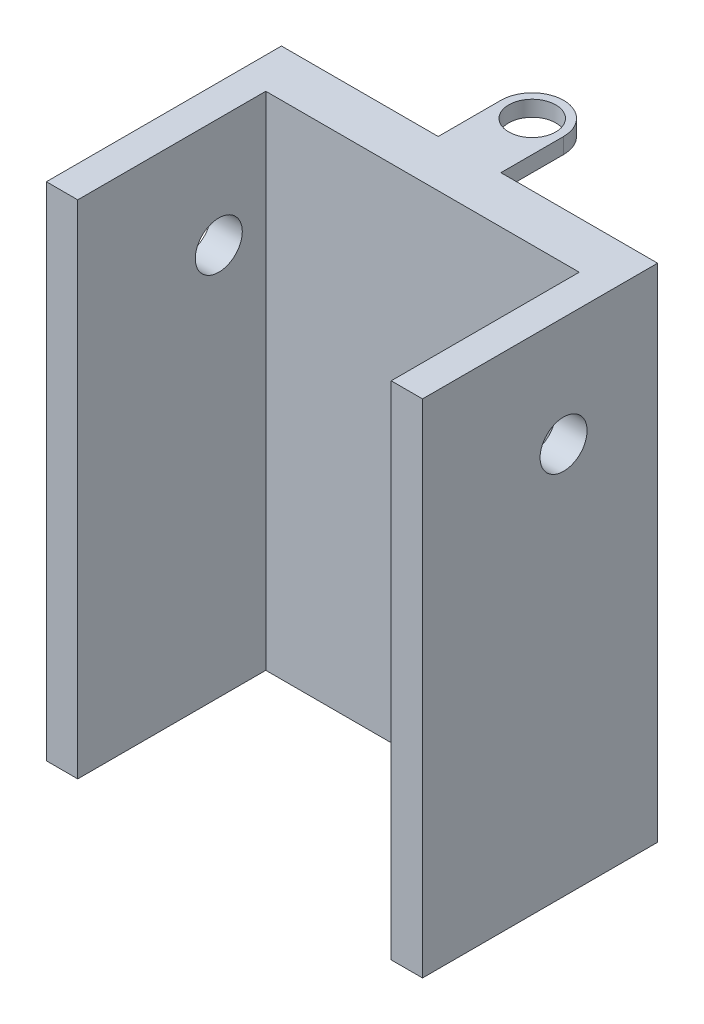
SolidWorks part; units mm, degrees
ref_plane "Plan de face" through (0, 0, 0) normal (0, 0, 1) x (1, 0, 0)
ref_plane "Plan de dessus" through (0, 0, 0) normal (0, 1, 0) x (1, 0, 0)
ref_plane "Plan de droite" through (0, 0, 0) normal (1, 0, 0) x (0, 0, -1)
sketch "Esquisse1" plane through (0, 0, 0) normal (0, 0, 1) x (1, 0, 0)
  line L1 (-10, 16) -> (10, 16)
  line L2 (-10, 16) -> (-10, -16)
  line L3 (-10, -16) -> (10, -16)
  line L4 (10, 16) -> (10, -16)
  line L5 (-10, 16) -> (10, -16) construction
  line L6 (-10, -16) -> (10, 16) construction
  point P0 (0, 0)
  dimension "D1" = 20
  dimension "D2" = 32
extrude "Boss.-Extru.1" add sketch "Esquisse1" along normal blind 3
sketch "Esquisse2" plane through (0, 0, 0) normal (0, 0, 1) x (1, 0, 0)
  line L0 (0, -20.8002) -> (0, 18.6821) construction
  line L1 (10, 16) -> (12, 16)
  line L2 (12, 16) -> (12, -16)
  line L3 (12, -16) -> (10, -16)
  line L4 (10, -16) -> (10, 16)
  line L5 (-12, -16) -> (-10, -16)
  line L6 (-12, 16) -> (-12, -16)
  line L7 (-10, 16) -> (-12, 16)
  line L8 (-10, -16) -> (-10, 16)
  dimension "D1" = 2
extrude "Boss.-Extru.2" add sketch "Esquisse2" along normal blind 15
sketch "Esquisse3" plane through (0, 0, 0) normal (1, 0, 0) x (0, 0, -1)
  circle A1 centre (-6, 9) radius 1.5 construction
  circle A2 centre (-6, 9) radius 1.5
extrude "Enlèv. mat.-Extru.1" cut sketch "Esquisse3" against normal through all both and the other way through all
sketch "Esquisse4" plane through (0, 0, 0) normal (0, 0, -1) x (-1, 0, 0)
  line L0 (-18.668, 9) -> (17.5142, 9) construction
  line L1 (-12, 16) -> (12, 16) construction
  text T0 "<b>FLAME</b>\r\n<b>DETECTION</b>\r\n<b>SENSOR</b>" font "Century Gothic" height in points 10
  point P5 (-8.9668, 9)
  point P6 (-10.3948, 7.8327)
  point P7 (0, 0)
  point P8 (-12, 9)
  point P9 (-9.581, 9)
  point P10 (-16.9647, 8.9399)
  point P11 (0, 0)
  point P12 (-12, 9)
  point P13 (-22.544, 8.9399)
  point P14 (-26.3941, 8.9399)
  point P15 (-22.1999, 8.9399)
  point P16 (-18.668, 8.9399)
  dimension "D1" = 7
extrude "Enlèv. mat.-Extru.2" cut sketch "Esquisse4" against normal blind 1
sketch "Esquisse5" plane through (0, 16, 0) normal (0, 1, 0) x (1, 0, 0)
  line L0 (-2, 0) -> (-2, 4)
  line L5 (12, 0) -> (-12, 0) construction
  line L6 (2, 4) -> (2, 0)
  line L7 (-2, 0) -> (2, 0)
  arc A2 (-2, 4) -> (2, 4) centre (0, 4) cw
  circle A3 centre (0, 4) radius 1.5
  dimension "D2" = 4
  dimension "D1" = 2
  dimension "D3" = 3
extrude "Boss.-Extru.3" add sketch "Esquisse5" against normal blind 1
